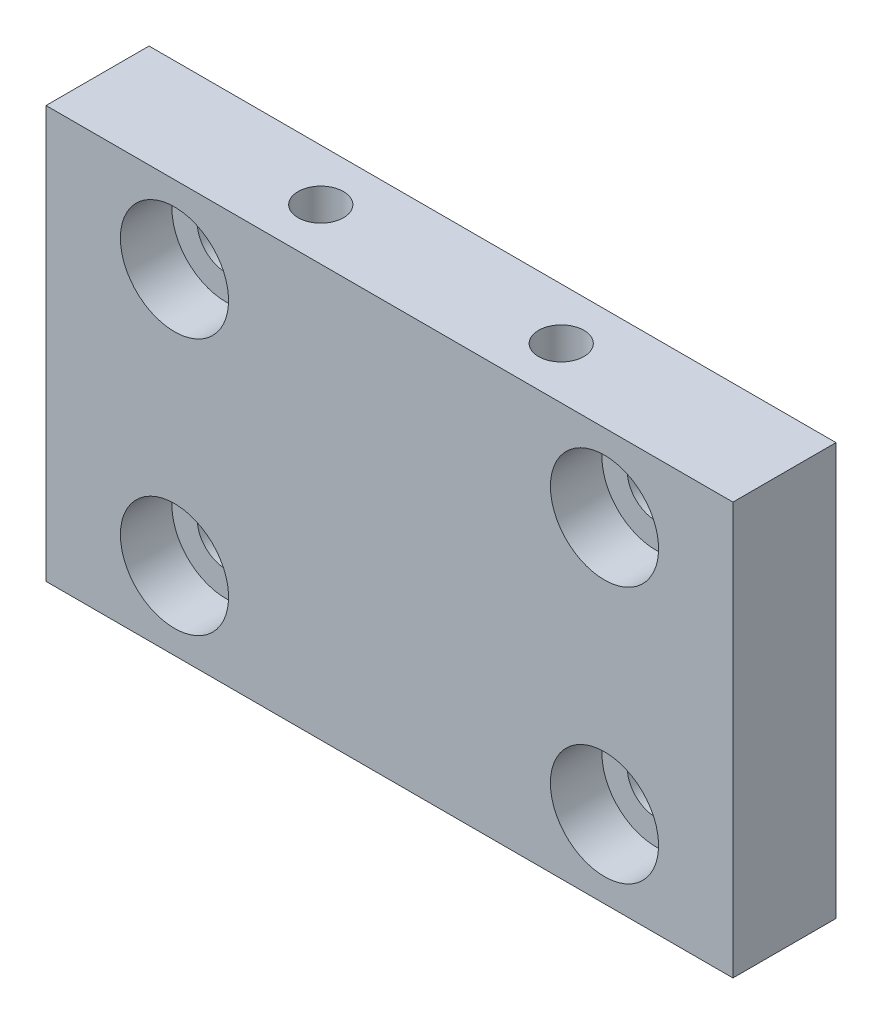
SolidWorks part; units mm, degrees
ref_plane "Front Plane" through (0, 0, 0) normal (0, 0, 1) x (1, 0, 0)
ref_plane "Top Plane" through (0, 0, 0) normal (0, 1, 0) x (1, 0, 0)
ref_plane "Right Plane" through (0, 0, 0) normal (1, 0, 0) x (0, 0, -1)
sketch "Sketch1" plane through (0, 0, 0) normal (0, 0, 1) x (1, 0, 0)
  line L1 (31.75, -19.05) -> (-31.75, -19.05)
  line L2 (31.75, -19.05) -> (31.75, 19.05)
  line L3 (31.75, 19.05) -> (-31.75, 19.05)
  line L4 (26, 20) -> (-26, 20)
  line L5 (-26, 20) -> (-26, -20)
  line L6 (-26, -20) -> (26, -20)
  line L7 (26, -20) -> (26, 20)
  line L8 (26, 20) -> (-26, 20) construction
  line L9 (-26, 20) -> (-26, -20) construction
  line L10 (-26, -20) -> (26, -20) construction
  line L11 (26, -20) -> (26, 20) construction
  line L12 (-31.75, -19.05) -> (-31.75, 19.05)
  line L13 (31.75, -19.05) -> (-31.75, 19.05) construction
  line L14 (31.75, 19.05) -> (-31.75, -19.05) construction
  circle A0 centre (-19.875, 11.875) radius 2.1 construction
  circle A1 centre (19.875, 11.875) radius 2.1 construction
  circle A2 centre (19.875, -11.875) radius 2.1 construction
  circle A3 centre (-19.875, -11.875) radius 2.1 construction
  circle A4 centre (-19.875, 11.875) radius 2.1 construction
  circle A5 centre (19.875, 11.875) radius 2.1 construction
  circle A6 centre (19.875, -11.875) radius 2.1 construction
  circle A7 centre (-19.875, -11.875) radius 2.1 construction
  circle A8 centre (-19.875, 11.875) radius 2.6543
  circle A9 centre (-19.875, -11.875) radius 2.6543
  circle A10 centre (19.875, -11.875) radius 2.6543
  circle A11 centre (19.875, 11.875) radius 2.6543
  point P16 (0, 0)
  dimension "D4" = 5.3086
  dimension "D2" = 38.1
  dimension "D3" = 63.5
  dimension "D1" = 0
extrude "Boss-Extrude1" add sketch "Sketch1" along normal blind 9.525
sketch "Sketch4" plane through (0, 0, 9.525) normal (0, 0, 1) x (1, 0, 0)
  circle A3 centre (19.875, 11.875) radius 2.1 construction
  circle A4 centre (-19.875, -11.875) radius 2.1 construction
  circle A5 centre (-19.875, 11.875) radius 2.1 construction
  circle A6 centre (19.875, 11.875) radius 2.1 construction
  circle A7 centre (19.875, -11.875) radius 2.1 construction
  circle A8 centre (19.875, -11.875) radius 5
  circle A9 centre (19.875, 11.875) radius 5
  circle A10 centre (-19.875, 11.875) radius 5
  circle A11 centre (-19.875, -11.875) radius 5
  circle A12 centre (19.875, -11.875) radius 2.1 construction
  circle A13 centre (-19.875, 11.875) radius 2.1 construction
  circle A14 centre (-19.875, -11.875) radius 2.1 construction
  dimension "D1" = 10
  dimension "D2" = 4.2
extrude "Cut-Extrude2" cut sketch "Sketch4" against normal blind 4.7625 and the other way through all
sketch "Sketch5" plane through (0, 0, 0) normal (0, 1, 0) x (1, 0, 0)
  line L0 (0, 0) -> (0, -9.525) construction
  line L1 (31.75, -9.525) -> (-31.75, -9.525) construction
  circle A0 centre (-11.1125, -4.7625) radius 2.1
  circle A2 centre (11.1125, -4.7625) radius 2.1
  point P10 (0, -4.7625)
  dimension "D2" = 4.2
  dimension "D1" = 22.225
extrude "Cut-Extrude3" cut sketch "Sketch5" against normal through all both and the other way through all
